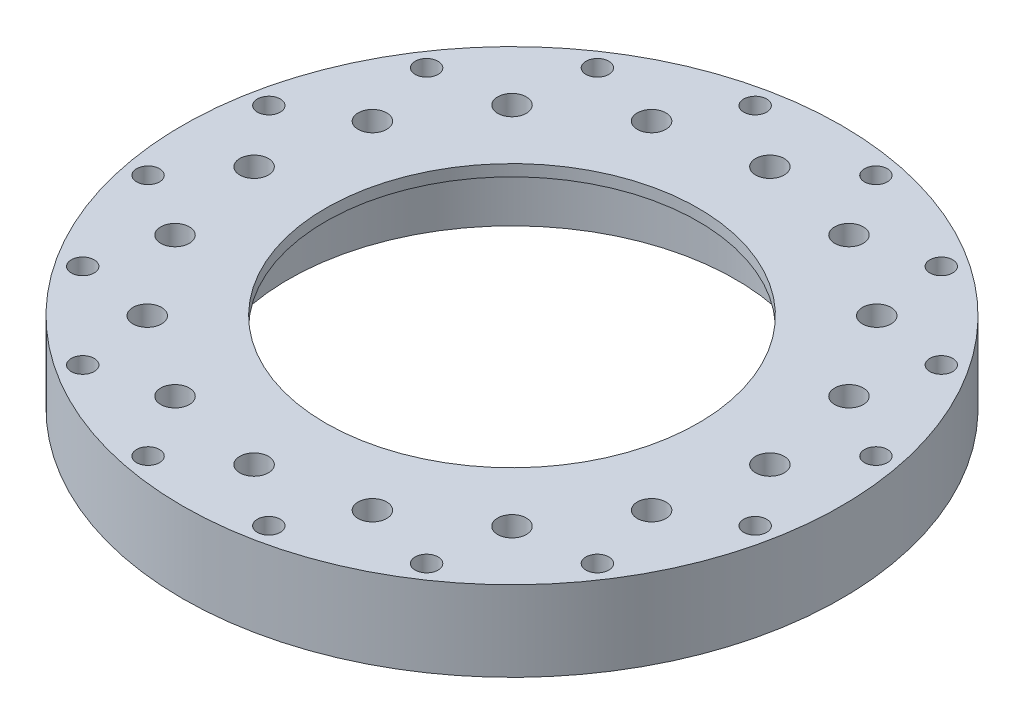
SolidWorks part; units mm, degrees
ref_plane "Front Plane" through (0, 0, 0) normal (0, 0, 1) x (1, 0, 0)
ref_plane "Top Plane" through (0, 0, 0) normal (0, 1, 0) x (1, 0, 0)
ref_plane "Right Plane" through (0, 0, 0) normal (1, 0, 0) x (0, 0, -1)
sketch "Sketch1" plane through (0, 0, 0) normal (0, 1, 0) x (1, 0, 0)
  line L0 (-10.5349, 52.9624) -> (0, 0) construction
  line L1 (0, 0) -> (24.6214, 0) construction
  circle A12 centre (0, 0) radius 39
  circle A13 centre (0, 0) radius 57.5
  circle A14 centre (0, 0) radius 54 construction
  circle A15 centre (-10.5349, 52.9624) radius 2
  circle A16 centre (10.5349, 52.9624) radius 2
  circle A17 centre (30.0008, 44.8994) radius 2
  circle A18 centre (44.8994, 30.0008) radius 2
  circle A19 centre (52.9624, 10.5349) radius 2
  circle A20 centre (52.9624, -10.5349) radius 2
  circle A21 centre (44.8994, -30.0008) radius 2
  circle A22 centre (30.0008, -44.8994) radius 2
  circle A23 centre (10.5349, -52.9624) radius 2
  circle A24 centre (-10.5349, -52.9624) radius 2
  circle A25 centre (-30.0008, -44.8994) radius 2
  circle A26 centre (-44.8994, -30.0008) radius 2
  circle A47 centre (-52.9624, -10.5349) radius 2
  circle A48 centre (-52.9624, 10.5349) radius 2
  circle A49 centre (-44.8994, 30.0008) radius 2
  circle A50 centre (-30.0008, 44.8994) radius 2
  point P21 (0, 0)
  point P28 (0, 0)
  point P56 (0, 0)
  point P60 (0, 0)
  dimension "D1" = 101.25
  dimension "D4" = 115
  dimension "D5" = 78
  dimension "D6" = 108
  dimension "D7" = 4
  dimension "D8" = 16
extrude "Boss-Extrude1" add sketch "Sketch1" along normal blind 12
sketch "Sketch2" plane through (0, 12, 0) normal (0, 1, 0) x (1, 0, 0)
  circle A0 centre (0, 0) radius 45 construction
  circle A1 centre (0, 45) radius 2.5
  circle A2 centre (17.2208, 41.5746) radius 2.5
  circle A3 centre (31.8198, 31.8198) radius 2.5
  circle A4 centre (41.5746, 17.2208) radius 2.5
  circle A5 centre (45, 0) radius 2.5
  circle A6 centre (41.5746, -17.2208) radius 2.5
  circle A7 centre (31.8198, -31.8198) radius 2.5
  circle A8 centre (17.2208, -41.5746) radius 2.5
  circle A9 centre (0, -45) radius 2.5
  circle A10 centre (-17.2208, -41.5746) radius 2.5
  circle A11 centre (-31.8198, -31.8198) radius 2.5
  circle A12 centre (-41.5746, -17.2208) radius 2.5
  circle A13 centre (-45, 0) radius 2.5
  circle A14 centre (-41.5746, 17.2208) radius 2.5
  circle A15 centre (-31.8198, 31.8198) radius 2.5
  circle A16 centre (-17.2208, 41.5746) radius 2.5
  point P27 (0, 0)
  dimension "D1" = 90
  dimension "D2" = 5
  dimension "D3" = 16
extrude "Cut-Extrude1" cut sketch "Sketch2" against normal blind 10
sketch "Sketch4" plane through (0, 0, 0) normal (0, 1, 0) x (1, 0, 0)
  circle A0 centre (0, 0) radius 45 construction
  circle A1 centre (0, 45) radius 5
  circle A2 centre (0, 45) radius 2.5
  circle A3 centre (17.2208, 41.5746) radius 2.5
  circle A4 centre (31.8198, 31.8198) radius 2.5
  circle A5 centre (41.5746, 17.2208) radius 2.5
  circle A6 centre (45, 0) radius 2.5
  circle A7 centre (41.5746, -17.2208) radius 2.5
  circle A8 centre (31.8198, -31.8198) radius 2.5
  circle A9 centre (17.2208, -41.5746) radius 2.5
  circle A10 centre (0, -45) radius 2.5
  circle A11 centre (-17.2208, -41.5746) radius 2.5
  circle A12 centre (-31.8198, -31.8198) radius 2.5
  circle A13 centre (17.2208, 41.5746) radius 5
  circle A14 centre (31.8198, 31.8198) radius 5
  circle A15 centre (41.5746, 17.2208) radius 5
  circle A16 centre (45, 0) radius 5
  circle A17 centre (41.5746, -17.2208) radius 5
  circle A18 centre (31.8198, -31.8198) radius 5
  circle A19 centre (17.2208, -41.5746) radius 5
  circle A20 centre (0, -45) radius 5
  circle A21 centre (-17.2208, -41.5746) radius 5
  circle A22 centre (-31.8198, -31.8198) radius 5
  circle A23 centre (-41.5746, -17.2208) radius 5
  circle A24 centre (-45, 0) radius 5
  circle A25 centre (-41.5746, 17.2208) radius 5
  circle A26 centre (-31.8198, 31.8198) radius 5
  circle A27 centre (-17.2208, 41.5746) radius 5
  circle A28 centre (-41.5746, -17.2208) radius 2.5
  circle A29 centre (-45, 0) radius 2.5
  circle A30 centre (-41.5746, 17.2208) radius 2.5
  circle A31 centre (-31.8198, 31.8198) radius 2.5
  circle A32 centre (-17.2208, 41.5746) radius 2.5
  point P29 (0, 0)
  point P50 (0, 0)
  dimension "D1" = 10
  dimension "D2" = 16
  dimension "D3" = 16
extrude "Boss-Extrude3" add sketch "Sketch4" against normal blind 0.4
sketch "Sketch6" plane through (0, 12, 0) normal (0, 1, 0) x (1, 0, 0)
  circle A0 centre (0, 0) radius 57.5
  circle A1 centre (0, 0) radius 32.5
  dimension "D1" = 65
extrude "Boss-Extrude4" add sketch "Sketch6" along normal blind 2
sketch "Sketch7" plane through (0, 0, 0) normal (0, -1, 0) x (1, 0, 0)
  circle A0 centre (0, 45) radius 2.5
  circle A1 centre (17.2208, 41.5746) radius 2.5
  circle A2 centre (31.8198, 31.8198) radius 2.5
  circle A3 centre (41.5746, 17.2208) radius 2.5
  circle A4 centre (45, 0) radius 2.5
  circle A5 centre (41.5746, -17.2208) radius 2.5
  circle A6 centre (31.8198, -31.8198) radius 2.5
  circle A7 centre (17.2208, -41.5746) radius 2.5
  circle A8 centre (0, -45) radius 2.5
  circle A9 centre (-17.2208, -41.5746) radius 2.5
  circle A10 centre (-31.8198, -31.8198) radius 2.5
  circle A11 centre (-41.5746, -17.2208) radius 2.5
  circle A12 centre (-45, 0) radius 2.5
  circle A13 centre (-41.5746, 17.2208) radius 2.5
  circle A14 centre (-31.8198, 31.8198) radius 2.5
  circle A15 centre (-17.2208, 41.5746) radius 2.5
  circle A16 centre (30.0008, 44.8994) radius 2
  circle A17 centre (44.8994, 30.0008) radius 2
  circle A18 centre (52.9624, 10.5349) radius 2
  circle A19 centre (52.9624, -10.5349) radius 2
  circle A20 centre (44.8994, -30.0008) radius 2
  circle A21 centre (30.0008, -44.8994) radius 2
  circle A22 centre (10.5349, -52.9624) radius 2
  circle A23 centre (-10.5349, -52.9624) radius 2
  circle A24 centre (-30.0008, -44.8994) radius 2
  circle A25 centre (-44.8994, -30.0008) radius 2
  circle A26 centre (-52.9624, -10.5349) radius 2
  circle A27 centre (-52.9624, 10.5349) radius 2
  circle A28 centre (-44.8994, 30.0008) radius 2
  circle A29 centre (-30.0008, 44.8994) radius 2
  circle A30 centre (-10.5349, 52.9624) radius 2
  circle A31 centre (10.5349, 52.9624) radius 2
  point P35 (0, 0)
  point P69 (0, 0)
extrude "Cut-Extrude2" cut sketch "Sketch7" against normal blind 58
